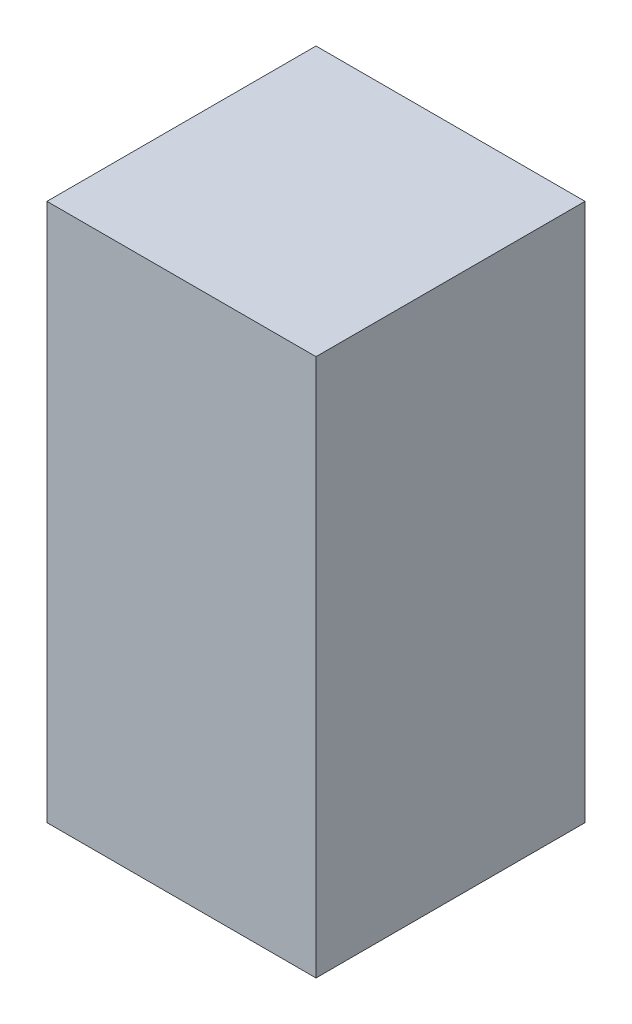
SolidWorks part; units mm, degrees
ref_plane "Front Plane" through (0, 0, 0) normal (0, 0, 1) x (1, 0, 0)
ref_plane "Top Plane" through (0, 0, 0) normal (0, 1, 0) x (1, 0, 0)
ref_plane "Right Plane" through (0, 0, 0) normal (1, 0, 0) x (0, 0, -1)
sketch "Sketch1" plane through (0, 0, 0) normal (0, 1, 0) x (1, 0, 0)
  line L1 (63.5, 63.5) -> (-63.5, 63.5)
  line L2 (63.5, 63.5) -> (63.5, -63.5)
  line L3 (63.5, -63.5) -> (-63.5, -63.5)
  line L4 (-63.5, 63.5) -> (-63.5, -63.5)
  line L5 (63.5, 63.5) -> (-63.5, -63.5) construction
  line L6 (63.5, -63.5) -> (-63.5, 63.5) construction
  point P0 (0, 0)
  dimension "D1" = 127
  dimension "D2" = 127
extrude "Boss-Extrude1" add sketch "Sketch1" along normal blind 254
